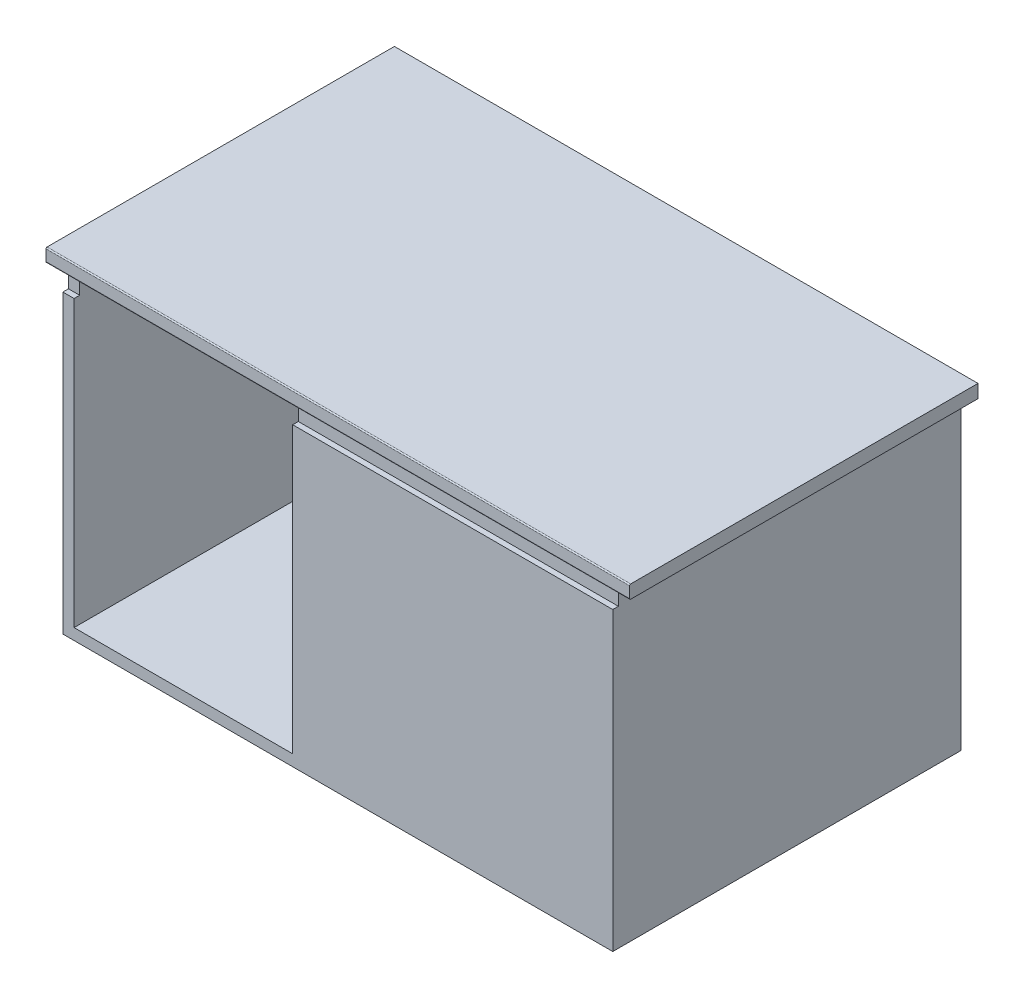
SolidWorks part; units mm, degrees
ref_plane "Front Plane" through (0, 0, 0) normal (0, 0, 1) x (1, 0, 0)
ref_plane "Top Plane" through (0, 0, 0) normal (0, 1, 0) x (1, 0, 0)
ref_plane "Right Plane" through (0, 0, 0) normal (1, 0, 0) x (0, 0, -1)
sketch "Sketch1" plane through (0, 0, 0) normal (0, 1, 0) x (1, 0, 0)
  line L1 (660, -394) -> (-660, -394)
  line L2 (660, -394) -> (660, 394)
  line L3 (660, 394) -> (-660, 394)
  line L4 (-660, -394) -> (-660, 394)
  line L5 (0, 394) -> (0, -394) construction
  line L6 (660, 0) -> (-660, 0) construction
  point P0 (0, 0)
  dimension "D1" = 788
  dimension "D2" = 1320
extrude "Boss-Extrude1" add sketch "Sketch1" along normal blind 738
sketch "Sketch5" plane through (0, 0, 394) normal (0, 0, 1) x (1, 0, 0)
  line L0 (-660, 738) -> (-660, 0) construction
  line L1 (-660, 708) -> (660, 708)
  line L2 (-660, 708) -> (-660, 670)
  line L3 (-660, 670) -> (660, 670)
  line L4 (660, 708) -> (660, 670)
  line L5 (0, 670) -> (0, 708) construction
  line L6 (-660, 689) -> (660, 689) construction
  line L7 (660, 738) -> (660, 0) construction
  line L8 (-660, 738) -> (660, 738) construction
  point P192 (0, 689)
  dimension "D1" = 30
  dimension "D2" = 38
extrude "Cut-Extrude1" cut sketch "Sketch5" against normal blind 12.7
fillet "Fillet2" radius 2.54 2 edges at (0, 708, 394) (0, 738, 394)
sketch "Sketch6" plane through (0, 0, 0) normal (0, -1, 0) x (1, 0, 0)
  line L0 (-660, 394) -> (660, 394) construction
  line L1 (660, -394) -> (621.9, -394)
  line L2 (660, -394) -> (660, 394)
  line L3 (660, 394) -> (621.9, 394)
  line L4 (621.9, -394) -> (621.9, 394)
  line L5 (660, -394) -> (-660, -394) construction
  line L6 (-660, 394) -> (-621.9, 394)
  line L7 (-660, 394) -> (-660, -394)
  line L8 (-660, -394) -> (-621.9, -394)
  line L9 (-621.9, 394) -> (-621.9, -394)
  dimension "D1" = 38.1
extrude "Cut-Extrude2" cut sketch "Sketch6" against normal up to surface (708 mm away) up to face at (0, 708, 386.38)
sketch "Sketch8" plane through (0, 0, 394) normal (0, 0, 1) x (1, 0, 0)
  line L1 (-596.5, 708) -> (-102, 708)
  line L2 (-596.5, 708) -> (-596.5, 25.4)
  line L3 (-596.5, 25.4) -> (-102, 25.4)
  line L4 (-102, 708) -> (-102, 25.4)
  line L5 (-621.9, 0) -> (621.9, 0) construction
  line L6 (-621.9, 670) -> (-621.9, 0) construction
  line L7 (621.9, 670) -> (621.9, 0) construction
  line L8 (660, 708) -> (-660, 708) construction
  dimension "D1" = 25.4
  dimension "D2" = 25.4
  dimension "D3" = 723.9
extrude "Cut-Extrude3" cut sketch "Sketch8" against normal offset from surface (762.6 mm away) 25.4 up to face at (0, 538.5, -394)
